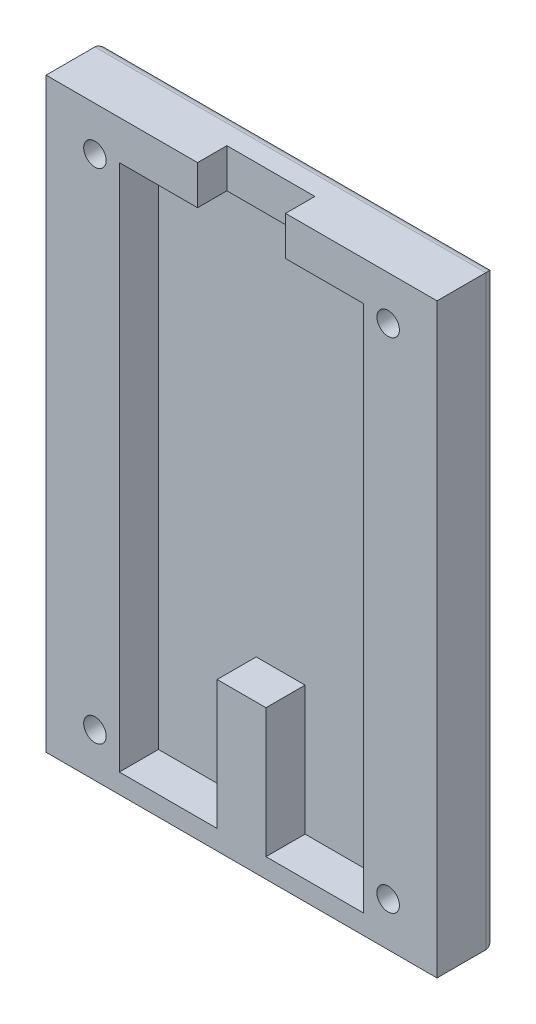
SolidWorks part; units mm, degrees
ref_plane "Front Plane" through (0, 0, 0) normal (1, 0, 0) x (0, 1, 0)
ref_plane "Top Plane" through (0, 0, 0) normal (0, 0, 1) x (0, 1, 0)
ref_plane "Right Plane" through (0, 0, 0) normal (0, 1, 0) x (-1, 0, 0)
sketch "Sketch1" plane through (0, 0, 0) normal (0, 0, 1) x (0, 1, 0)
  line L0 (0, -20) -> (60, -20) construction
  line L1 (0, 0) -> (60, 0)
  line L2 (0, 0) -> (0, -40)
  line L3 (0, -40) -> (60, -40)
  line L4 (60, 0) -> (60, -40)
  dimension "D1" = 60
  dimension "D2" = 40
extrude "Boss-Extrude1" add sketch "Sketch1" along normal blind 6
sketch "Sketch3" plane through (0, 0, 6) normal (0, 0, 1) x (1, 0, 0)
  line L0 (0, 55.5) -> (40, 55.5) construction
  line L1 (0, 60) -> (0, 0) construction
  line L2 (40, 0) -> (40, 60) construction
  line L3 (0, 4.5) -> (40, 4.5) construction
  line L4 (0, 30) -> (40, 30) construction
  line L5 (20, 60) -> (20, 0) construction
  line L6 (40, 60) -> (0, 60) construction
  line L7 (0, 0) -> (40, 0) construction
  circle A0 centre (5, 4.5) radius 1.15
  circle A1 centre (35, 4.5) radius 1.15
  circle A2 centre (5, 55.5) radius 1.15
  circle A3 centre (35, 55.5) radius 1.15
  dimension "D5" = 2.3
  dimension "D6" = 2.3
  dimension "D7" = 2.3
  dimension "D8" = 2.3
  dimension "D1" = 25.5
  dimension "D2" = 25.5
  dimension "D3" = 15
  dimension "D4" = 15
  dimension "D9" = 15
  dimension "D10" = 15
extrude "Cut-Extrude2" cut sketch "Sketch3" against normal through all
sketch "Sketch12" plane through (0, 0, 6) normal (0, 0, 1) x (1, 0, 0)
  line L0 (20, 60) -> (20, 0) construction
  line L1 (40, 60) -> (0, 60) construction
  line L2 (0, 0) -> (40, 0) construction
  line L4 (32.5, 56) -> (7.5, 56)
  line L5 (32.5, 56) -> (32.5, 15.2)
  line L6 (32.5, 15.2) -> (7.5, 15.2)
  line L7 (7.5, 56) -> (7.5, 15.2)
  line L8 (32.5, 56) -> (7.5, 15.2) construction
  line L9 (32.5, 15.2) -> (7.5, 56) construction
  point P6 (20, 35.6)
  dimension "D1" = 15.2
  dimension "D2" = 25
  dimension "D3" = 4
extrude "Cut-Extrude10" cut sketch "Sketch12" against normal blind 4
sketch "Sketch13" plane through (0, 0, 0) normal (0, 0, -1) x (1, 0, 0)
  line L0 (5, -4.5) -> (35, -4.5) construction
  line L1 (5, -55.5) -> (35, -55.5) construction
  line L3 (7.4249, -55.5) -> (6.2124, -53.4)
  line L4 (6.2124, -53.4) -> (3.7876, -53.4)
  line L5 (3.7876, -53.4) -> (2.5751, -55.5)
  line L6 (2.5751, -55.5) -> (3.7876, -57.6)
  line L7 (3.7876, -57.6) -> (6.2124, -57.6)
  line L8 (6.2124, -57.6) -> (7.4249, -55.5)
  line L9 (32.5751, -55.5) -> (33.7876, -57.6)
  line L10 (33.7876, -57.6) -> (36.2124, -57.6)
  line L11 (36.2124, -57.6) -> (37.4249, -55.5)
  line L12 (37.4249, -55.5) -> (36.2124, -53.4)
  line L13 (36.2124, -53.4) -> (33.7876, -53.4)
  line L14 (33.7876, -53.4) -> (32.5751, -55.5)
  line L15 (7.4249, -4.5) -> (6.2124, -2.4)
  line L16 (6.2124, -2.4) -> (3.7876, -2.4)
  line L17 (3.7876, -2.4) -> (2.5751, -4.5)
  line L18 (2.5751, -4.5) -> (3.7876, -6.6)
  line L19 (3.7876, -6.6) -> (6.2124, -6.6)
  line L20 (6.2124, -6.6) -> (7.4249, -4.5)
  line L21 (32.5751, -4.5) -> (33.7876, -6.6)
  line L22 (33.7876, -6.6) -> (36.2124, -6.6)
  line L23 (36.2124, -6.6) -> (37.4249, -4.5)
  line L24 (37.4249, -4.5) -> (36.2124, -2.4)
  line L25 (36.2124, -2.4) -> (33.7876, -2.4)
  line L26 (33.7876, -2.4) -> (32.5751, -4.5)
  circle A0 centre (5, -55.5) radius 2.1 construction
  circle A1 centre (35, -55.5) radius 2.1 construction
  circle A2 centre (5, -4.5) radius 2.1 construction
  circle A3 centre (35, -4.5) radius 2.1 construction
  dimension "D1" = 4.2
  dimension "D2" = 4.2
  dimension "D3" = 4.2
  dimension "D4" = 4.2
extrude "Cut-Extrude11" cut sketch "Sketch13" against normal blind 2.8
fillet "Fillet1" radius 1 4 edges at (40, 30, 0) (20, 0, 0) (0, 30, 0) (20, 60, 0)
sketch "Sketch14" plane through (0, 0, 6) normal (0, 0, 1) x (1, 0, 0)
  line L0 (7.5, 15.2) -> (32.5, 15.2) construction
  line L1 (7.5, 15.2) -> (17.5, 15.2)
  line L2 (7.5, 15.2) -> (7.5, 2)
  line L3 (7.5, 2) -> (17.5, 2)
  line L4 (17.5, 15.2) -> (17.5, 2)
  line L5 (32.5, 15.2) -> (22.5, 15.2)
  line L6 (32.5, 15.2) -> (32.5, 2)
  line L7 (32.5, 2) -> (22.5, 2)
  line L8 (22.5, 15.2) -> (22.5, 2)
  line L9 (7.5, 15.2) -> (32.5, 15.2) construction
  line L10 (0, 0) -> (40, 0) construction
  line L11 (32.5, 15.2) -> (32.5, 56) construction
  point P17 (0, 0)
  dimension "D1" = 2
  dimension "D2" = 5
extrude "Cut-Extrude12" cut sketch "Sketch14" against normal blind 4
sketch "Sketch15" plane through (0, 0, 6) normal (0, 0, 1) x (1, 0, 0)
  line L0 (20, 60) -> (20, 56) construction
  line L1 (40, 60) -> (0, 60) construction
  line L2 (32.5, 56) -> (7.5, 56) construction
  line L3 (32.5, 56) -> (7.5, 56) construction
  line L4 (24.5, 56) -> (15.5, 56)
  line L5 (24.5, 56) -> (24.5, 60)
  line L6 (24.5, 60) -> (15.5, 60)
  line L7 (15.5, 56) -> (15.5, 60)
  line L8 (24.5, 56) -> (15.5, 60) construction
  line L9 (24.5, 60) -> (15.5, 56) construction
  point P6 (20, 58)
  dimension "D1" = 9
extrude "Cut-Extrude13" cut sketch "Sketch15" against normal blind 3
